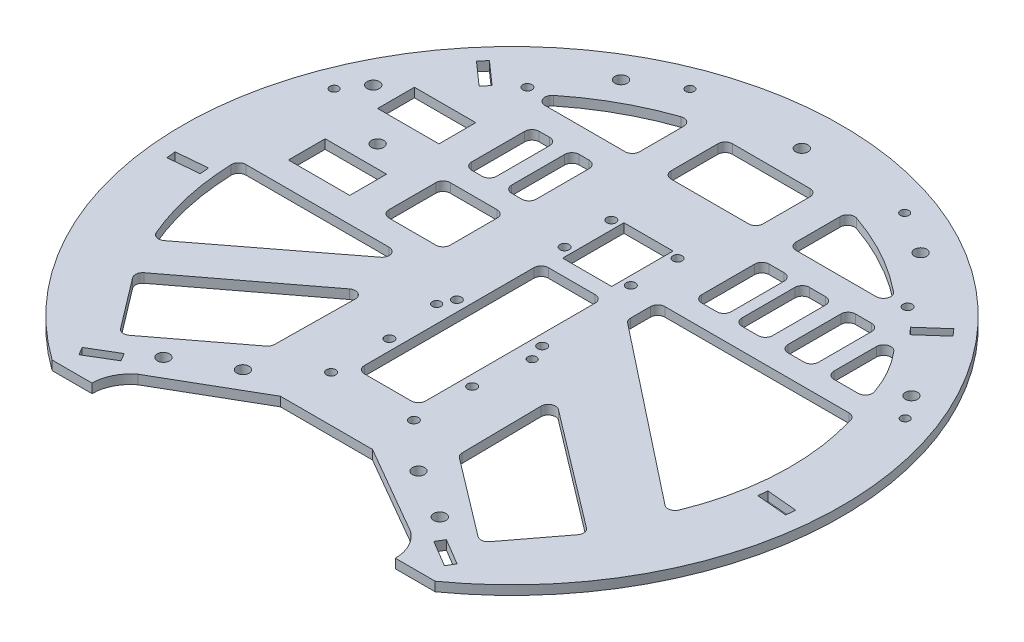
SolidWorks part; units mm, degrees
ref_plane "Front Plane" through (0, 0, 0) normal (0, 0, 1) x (1, 0, 0)
ref_plane "Top Plane" through (0, 0, 0) normal (0, 1, 0) x (1, 0, 0)
ref_plane "Right Plane" through (0, 0, 0) normal (1, 0, 0) x (0, 0, -1)
sketch "Sketch3" plane through (0, 0, 0) normal (0, 1, 0) x (1, 0, 0)
  line L0 (62.45, -87.5) -> (49.45, -87.5)
  line L5 (7.6386, -40.5) -> (-7.6386, -40.5)
  line L6 (-10, -38.1386) -> (-10, 17.1386)
  line L7 (-7.6386, 19.5) -> (7.6386, 19.5)
  line L8 (10, 17.1386) -> (10, -38.1386)
  line L9 (63.1175, 36.8614) -> (63.1175, 54.1386)
  line L10 (0, 107.5) -> (0, -126.7072) construction
  line L13 (-34.0506, -18.9275) -> (-72.1189, -47.8376)
  line L14 (-37.9392, -4.9265) -> (-77.8771, -35.4832)
  line L15 (-39.3741, -0.6896) -> (-86.0847, -0.6896)
  line L16 (-30, 9.8718) -> (-30, 25.149)
  line L17 (-32.3614, 27.5104) -> (-47.6386, 27.5104)
  line L18 (-50, 25.149) -> (-50, 9.8718)
  line L19 (-47.6386, 7.5104) -> (-32.3614, 7.5104)
  line L20 (-60.4278, 7.5104) -> (-60.4278, 19.5104)
  line L21 (-60.4278, 19.5104) -> (-80.4278, 19.5104)
  line L22 (-80.4278, 19.5104) -> (-80.4278, 7.5104)
  line L23 (-80.4278, 7.5104) -> (-60.4278, 7.5104)
  line L28 (-60.4278, 36.6052) -> (-60.4278, 48.6052)
  line L29 (-60.4278, 48.6052) -> (-80.4278, 48.6052)
  line L30 (-30.2612, -20.8387) -> (-30.5985, -46.8494)
  line L31 (-80.4278, 48.6052) -> (-80.4278, 36.6052)
  line L32 (-80.4278, 36.6052) -> (-60.4278, 36.6052)
  line L33 (-41.8825, 36.8614) -> (-41.8825, 54.1386)
  line L34 (-44.2439, 56.5) -> (-47.6386, 56.5)
  line L35 (-50, 54.1386) -> (-50, 36.8614)
  line L36 (-47.6386, 34.5) -> (-44.2439, 34.5)
  line L41 (8, 24.5) -> (-8, 24.5)
  line L43 (-8, 44.5) -> (8, 44.5)
  line L44 (8, 44.5) -> (8, 24.5)
  line L50 (20, 18.6456) -> (20, 25.1386)
  line L51 (22.3614, 27.5) -> (82.3868, 27.5)
  line L52 (78.3282, 34.5) -> (70.479, 34.5)
  line L53 (68.1175, 36.8614) -> (68.1175, 50.6943)
  line L54 (60.7561, 56.5) -> (55.479, 56.5)
  line L55 (53.1175, 54.1386) -> (53.1175, 36.8614)
  line L56 (55.479, 34.5) -> (60.7561, 34.5)
  line L57 (45.7561, 34.5) -> (40.479, 34.5)
  line L58 (38.1175, 36.8614) -> (38.1175, 54.1386)
  line L59 (40.479, 56.5) -> (45.7561, 56.5)
  line L60 (30.2612, -20.8387) -> (30.5985, -46.8494)
  line L68 (-25.5, 67.1081) -> (-25.5, 81.5083)
  line L81 (34.0506, -18.9275) -> (72.1189, -47.8376)
  line L82 (78.4833, -28.5913) -> (20.8997, 16.7909)
  line L83 (-54.0033, 64.7467) -> (-27.8614, 64.7467)
  line L85 (48.1175, 36.8614) -> (48.1175, 54.1386)
  line L86 (25.5, 67.1081) -> (25.5, 81.5083)
  line L87 (54.0033, 64.7467) -> (27.8614, 64.7467)
  line L88 (-15, -60.5) -> (-44.4449, -77.5)
  line L89 (-15, -60.5) -> (15, -60.5)
  line L90 (15, -60.5) -> (44.4449, -77.5)
  line L91 (-49.45, -87.5) -> (-62.45, -87.5)
  line L95 (-31.5315, -48.6993) -> (-56.858, -67.9329)
  line L96 (-72.5713, -51.1463) -> (-60.1667, -67.4805)
  line L97 (31.5315, -48.6993) -> (56.858, -67.9329)
  line L98 (72.5713, -51.1463) -> (60.1667, -67.4805)
  line L104 (-36.9576, 54.1386) -> (-36.9576, 36.8614)
  line L105 (-34.5962, 56.5) -> (-31.3191, 56.5)
  line L106 (-34.5962, 34.5) -> (-31.3191, 34.5)
  line L107 (-28.9576, 54.1386) -> (-28.9576, 36.8614)
  line L112 (34.6175, 54.1386) -> (34.6175, 36.8614)
  line L113 (32.2561, 56.5) -> (27.3488, 56.5)
  line L114 (32.2561, 34.5) -> (27.3488, 34.5)
  line L115 (24.9873, 54.1386) -> (24.9873, 36.8614)
  line L116 (-15, 66.8614) -> (-15, 82.1386)
  line L117 (-12.6386, 64.5) -> (12.6386, 64.5)
  line L118 (-12.6386, 84.5) -> (12.6386, 84.5)
  line L119 (15, 66.8614) -> (15, 82.1386)
  line L120 (-8, 44.5) -> (-8, 24.5)
  arc A5 (-62.45, -87.5) -> (62.45, -87.5) centre (0, 0) cw
  arc A9 (-81.4863, -34.5291) -> (-88.4446, -3.1347) centre (0, 0) cw
  arc A10 (-55.4838, 68.9478) -> (-28.6252, 83.7427) centre (0, 0) cw
  arc A12 (72.2775, 52.2245) -> (80.5643, 37.6206) centre (38.2127, 23.2419) cw
  arc A13 (82.1308, -27.6301) -> (84.6469, 25.8229) centre (8.0792, 2.6412) ccw
  circle A22 centre (-28.6195, -59.1256) radius 2
  circle A25 centre (-45.0553, -68.6148) radius 2
  circle A27 centre (28.6192, -59.1254) radius 2
  circle A31 centre (87.7501, 42.499) radius 2
  circle A34 centre (48.8392, 84.3859) radius 2
  circle A37 centre (-15.5888, -8.9994) radius 1.4
  circle A39 centre (-70.4278, 26.6052) radius 2
  circle A41 centre (-87.7498, 42.4997) radius 2
  circle A45 centre (-48.8392, 84.3859) radius 2
  arc A46 (55.4838, 68.9478) -> (28.6252, 83.7427) centre (0, 0) ccw
  circle A47 centre (45.0549, -68.6146) radius 2
  circle A48 centre (-62, 67) radius 1.5
  circle A50 centre (62, 67) radius 1.5
  circle A51 centre (0, 94.5) radius 2
  arc A55 (-49.45, -87.5) -> (-44.4449, -77.5) centre (-36.9576, -87.5) cw
  arc A56 (49.45, -87.5) -> (44.4449, -77.5) centre (36.9576, -87.5) ccw
  circle A58 centre (15.5885, -8.9999) radius 1.4
  circle A59 centre (13.5, -26.5) radius 1.5
  circle A60 centre (-13.5, -26.5) radius 1.5
  circle A61 centre (-13.5, -4.5) radius 1.5
  circle A62 centre (13.5, -3.6504) radius 1.5
  circle A63 centre (-10.795, 43.18) radius 1.5
  circle A64 centre (10.795, 43.18) radius 1.5
  circle A65 centre (-10.795, 27.94) radius 1.5
  circle A66 centre (10.795, 27.94) radius 1.5
  circle A67 centre (-13.5, -45.5) radius 1.5
  circle A68 centre (13.5, -45.5) radius 1.5
  arc A69 (12.6386, 64.5) -> (15, 66.8614) centre (12.6386, 66.8614) ccw
  arc A70 (12.6386, 84.5) -> (15, 82.1386) centre (12.6386, 82.1386) cw
  arc A71 (-15, 66.8614) -> (-12.6386, 64.5) centre (-12.6386, 66.8614) ccw
  arc A72 (-15, 82.1386) -> (-12.6386, 84.5) centre (-12.6386, 82.1386) cw
  arc A73 (-27.8614, 64.7467) -> (-25.5, 67.1081) centre (-27.8614, 67.1081) ccw
  arc A74 (-55.4838, 68.9478) -> (-54.0033, 64.7467) centre (-54.0033, 67.1081) ccw
  arc A75 (-28.6252, 83.7427) -> (-25.5, 81.5083) centre (-27.8614, 81.5083) cw
  arc A76 (78.3282, 34.5) -> (80.5643, 37.6206) centre (78.3282, 36.8614) ccw
  arc A77 (68.1175, 36.8614) -> (70.479, 34.5) centre (70.479, 36.8614) ccw
  arc A78 (68.1175, 50.6943) -> (72.2775, 52.2245) centre (70.479, 50.6943) cw
  arc A79 (60.7561, 56.5) -> (63.1175, 54.1386) centre (60.7561, 54.1386) cw
  arc A80 (60.7561, 34.5) -> (63.1175, 36.8614) centre (60.7561, 36.8614) ccw
  arc A81 (53.1175, 36.8614) -> (55.479, 34.5) centre (55.479, 36.8614) ccw
  arc A82 (53.1175, 54.1386) -> (55.479, 56.5) centre (55.479, 54.1386) cw
  arc A83 (45.7561, 56.5) -> (48.1175, 54.1386) centre (45.7561, 54.1386) cw
  arc A84 (45.7561, 34.5) -> (48.1175, 36.8614) centre (45.7561, 36.8614) ccw
  arc A85 (38.1175, 36.8614) -> (40.479, 34.5) centre (40.479, 36.8614) ccw
  arc A86 (38.1175, 54.1386) -> (40.479, 56.5) centre (40.479, 54.1386) cw
  arc A87 (32.2561, 34.5) -> (34.6175, 36.8614) centre (32.2561, 36.8614) ccw
  arc A88 (32.2561, 56.5) -> (34.6175, 54.1386) centre (32.2561, 54.1386) cw
  arc A89 (24.9873, 36.8614) -> (27.3488, 34.5) centre (27.3488, 36.8614) ccw
  arc A90 (24.9873, 54.1386) -> (27.3488, 56.5) centre (27.3488, 54.1386) cw
  arc A91 (-32.3614, 27.5104) -> (-30, 25.149) centre (-32.3614, 25.149) cw
  arc A92 (-32.3614, 7.5104) -> (-30, 9.8718) centre (-32.3614, 9.8718) ccw
  arc A93 (-47.6386, 7.5104) -> (-50, 9.8718) centre (-47.6386, 9.8718) cw
  arc A94 (-50, 25.149) -> (-47.6386, 27.5104) centre (-47.6386, 25.149) cw
  arc A95 (-31.3191, 56.5) -> (-28.9576, 54.1386) centre (-31.3191, 54.1386) cw
  arc A96 (-31.3191, 34.5) -> (-28.9576, 36.8614) centre (-31.3191, 36.8614) ccw
  arc A97 (-36.9576, 36.8614) -> (-34.5962, 34.5) centre (-34.5962, 36.8614) ccw
  arc A98 (-36.9576, 54.1386) -> (-34.5962, 56.5) centre (-34.5962, 54.1386) cw
  arc A99 (-44.2439, 56.5) -> (-41.8825, 54.1386) centre (-44.2439, 54.1386) cw
  arc A100 (-44.2439, 34.5) -> (-41.8825, 36.8614) centre (-44.2439, 36.8614) ccw
  arc A101 (-47.6386, 34.5) -> (-50, 36.8614) centre (-47.6386, 36.8614) cw
  arc A102 (-50, 54.1386) -> (-47.6386, 56.5) centre (-47.6386, 54.1386) cw
  arc A103 (54.0033, 64.7467) -> (55.4838, 68.9478) centre (54.0033, 67.1081) ccw
  arc A104 (27.8614, 64.7467) -> (25.5, 67.1081) centre (27.8614, 67.1081) cw
  arc A105 (25.5, 81.5083) -> (28.6252, 83.7427) centre (27.8614, 81.5083) cw
  arc A106 (-39.3741, -0.6896) -> (-37.9392, -4.9265) centre (-39.3741, -3.051) cw
  arc A107 (-77.8771, -35.4832) -> (-81.4863, -34.5291) centre (-79.312, -33.6078) cw
  arc A108 (-88.4446, -3.1347) -> (-86.0847, -0.6896) centre (-86.0847, -3.051) cw
  arc A109 (-72.5713, -51.1463) -> (-72.1189, -47.8376) centre (-70.6907, -49.7182) cw
  arc A110 (-60.1667, -67.4805) -> (-56.858, -67.9329) centre (-58.2862, -66.0523) ccw
  arc A111 (-31.5315, -48.6993) -> (-30.5985, -46.8494) centre (-32.9597, -46.8188) ccw
  arc A112 (-34.0506, -18.9275) -> (-30.2612, -20.8387) centre (-32.6224, -20.8081) cw
  arc A113 (-10, 17.1386) -> (-7.6386, 19.5) centre (-7.6386, 17.1386) cw
  arc A114 (7.6386, 19.5) -> (10, 17.1386) centre (7.6386, 17.1386) cw
  arc A115 (10, -38.1386) -> (7.6386, -40.5) centre (7.6386, -38.1386) cw
  arc A116 (-10, -38.1386) -> (-7.6386, -40.5) centre (-7.6386, -38.1386) ccw
  arc A117 (72.1189, -47.8376) -> (72.5713, -51.1463) centre (70.6907, -49.7182) cw
  arc A118 (56.858, -67.9329) -> (60.1667, -67.4805) centre (58.2862, -66.0523) ccw
  arc A119 (30.5985, -46.8494) -> (31.5315, -48.6993) centre (32.9597, -46.8188) ccw
  arc A120 (30.2612, -20.8387) -> (34.0506, -18.9275) centre (32.6224, -20.8081) cw
  arc A121 (78.4833, -28.5913) -> (82.1308, -27.6301) centre (79.945, -26.7366) ccw
  arc A122 (84.6469, 25.8229) -> (82.3868, 27.5) centre (82.3868, 25.1386) ccw
  arc A123 (20, 18.6456) -> (20.8997, 16.7909) centre (22.3614, 18.6456) ccw
  arc A124 (20, 25.1386) -> (22.3614, 27.5) centre (22.3614, 25.1386) cw
  point P45 (0, -60.5)
  point P48 (0, 64.6145)
  point P49 (0, 84.5)
  point P51 (0, 84.7467)
  point P62 (0, 107.5)
  point P90 (0, 24.5)
  point P91 (0, 44.5)
  point P93 (15, 64.5)
  point P97 (15, 84.5)
  point P104 (-25.5, 64.7467)
  point P109 (-60.3334, 64.7467)
  point P113 (-25.5, 84.7467)
  point P150 (38.1175, 34.5)
  point P155 (34.6175, 34.5)
  point P172 (-28.9576, 56.5)
  point P179 (-36.9576, 56.5)
  point P190 (60.3334, 64.7467)
  point P193 (25.5, 64.7467)
  point P196 (25.5, 84.7467)
  point P202 (-80.2546, -37.3023)
  point P209 (-73.9995, -49.2657)
  point P212 (-58.7386, -69.3611)
  point P215 (-30.6134, -48.0021)
  point P218 (-30.1985, -16.0021)
  point P233 (73.9995, -49.2657)
  point P238 (58.7386, -69.3611)
  point P243 (30.6134, -48.0021)
  point P246 (30.1985, -16.0021)
  point P249 (80.8953, -30.4921)
  point P256 (20, 17.5)
  point P263 (20, 27.5)
  dimension "D8" = 3
  dimension "D9" = 91.2853
  dimension "D10" = 30
  dimension "D11" = 27
  dimension "D12" = 150
  dimension "D13" = 34
  dimension "D14" = 13
  dimension "D15" = 155
  dimension "D16" = 8
  dimension "D17" = 8
  dimension "D18" = 13.5
  dimension "D19" = 34
  dimension "D20" = 8
  dimension "D21" = 8
  dimension "D22" = 20
  dimension "D6" = 3
  dimension "D7" = 62
  dimension "D23" = 3
  dimension "D24" = 3
  dimension "D27" = 8
  dimension "D33" = 107.5
  dimension "D40" = 19
  dimension "D28" = 23
  dimension "D42" = 13.5
  dimension "D43" = 22
  dimension "D44" = 13.5
  dimension "D45" = 3
  dimension "D46" = 3
  dimension "D47" = 3
  dimension "D48" = 3
  dimension "D49" = 15.24
  dimension "D50" = 10.795
  dimension "D51" = 10.795
  dimension "D52" = 22.8496
  dimension "D55" = 3
  dimension "D54" = 27
  dimension "D56" = 3
  dimension "D57" = 13.5
  dimension "D58" = 13.5
  dimension "D59" = 15
  dimension "D60" = 15
  dimension "D63" = 2.3614
  dimension "D64" = 2.3614
  dimension "D65" = 2.3614
  dimension "D67" = 8.44
  dimension "D3" = 10
  dimension "D4" = 55
  dimension "D5" = 3.5
  dimension "D25" = 32
  dimension "D26" = 8
  dimension "D29" = 20
  dimension "D30" = 25.5
  dimension "D31" = 150
  dimension "D32" = 20
  dimension "D34" = 20
  dimension "D35" = 20
  dimension "D36" = 13.5
  dimension "D37" = 13.5
  dimension "D38" = 8.2
  dimension "D39" = 8.2
  dimension "D41" = 98.9
  dimension "D53" = 20
  dimension "D61" = 20
  dimension "D62" = 12
  dimension "D66" = 5
extrude "Tapa" add sketch "Sketch3" along normal blind 3
sketch "Sketch4" plane through (0, 3, 0) normal (0, 1, 0) x (1, 0, 0)
  line L0 (0, 0) -> (0, -88.7396) construction
  circle A1 centre (-93.1034, 35.1) radius 1.4
  circle A5 centre (35, 93.0342) radius 1.4
  circle A7 centre (58, -78.9937) radius 1.4
  circle A8 centre (0, 0) radius 107.5
  arc A9 (62.45, -87.5) -> (-62.45, -87.5) centre (0, 0) ccw construction
  circle A10 centre (-35, 93.0342) radius 1.4
  circle A11 centre (93.1034, 35.1) radius 1.4
  circle A13 centre (-58, -78.9937) radius 1.4
  dimension "D2" = 2.8
  dimension "D4" = 99.4
  dimension "D6" = 99.5
  dimension "D7" = 2.8
  dimension "D10" = 98
  dimension "D12" = 58
  dimension "D13" = 2.8
  dimension "D5" = 35
  dimension "D11" = 35.1
extrude "Holes de soportes" cut sketch "Sketch4" against normal blind 30
sketch "Sketch6" plane through (0, 3, 0) normal (0, 1, 0) x (1, 0, 0)
  line L0 (0, 138.3374) -> (0, -97.2111) construction
  line L1 (90.9, -10.7432) -> (91.1724, -7.7556)
  line L2 (101.1724, -8.6674) -> (91.1724, -7.7556)
  line L3 (100.9, -11.655) -> (90.9, -10.7432)
  line L4 (100.9, -11.655) -> (101.1724, -8.6674)
  line L5 (70.2156, 59.4796) -> (68.2269, 61.7257)
  line L6 (75.7142, 68.3546) -> (68.2269, 61.7257)
  line L7 (77.7028, 66.1084) -> (70.2156, 59.4796)
  line L8 (77.7028, 66.1084) -> (75.7142, 68.3546)
  line L9 (-100.9, -11.655) -> (-101.1724, -8.6674)
  line L10 (-100.9, -11.655) -> (-90.9, -10.7432)
  line L11 (-101.1724, -8.6674) -> (-91.1724, -7.7556)
  line L12 (-90.9, -10.7432) -> (-91.1724, -7.7556)
  line L13 (-77.7028, 66.1084) -> (-75.7142, 68.3546)
  line L14 (-75.7142, 68.3546) -> (-68.2269, 61.7257)
  line L15 (-77.7028, 66.1084) -> (-70.2156, 59.4796)
  line L16 (-70.2156, 59.4796) -> (-68.2269, 61.7257)
  line L17 (-61.1276, -79.0484) -> (-52.5405, -73.9239)
  line L18 (-52.5405, -73.9239) -> (-51.0031, -76.5)
  line L19 (-51.0031, -76.5) -> (-59.5902, -81.6246)
  line L20 (-59.5902, -81.6246) -> (-61.1276, -79.0484)
  line L21 (-62.45, -87.5) -> (-49.45, -87.5) construction
  line L22 (59.5902, -81.6246) -> (61.1276, -79.0484)
  line L23 (51.0031, -76.5) -> (59.5902, -81.6246)
  line L24 (52.5405, -73.9239) -> (51.0031, -76.5)
  line L25 (61.1276, -79.0484) -> (52.5405, -73.9239)
  circle A0 centre (0, 0) radius 107.5
  arc A1 (62.45, -87.5) -> (-62.45, -87.5) centre (0, 0) ccw construction
  dimension "D1" = 92
  dimension "D2" = 91.5
  dimension "D3" = 3
  dimension "D4" = 3
  dimension "D5" = 10
  dimension "D6" = 10
  dimension "D7" = 3
  dimension "D8" = 10
  dimension "D9" = 10
  dimension "D10" = 3
  dimension "D11" = 77.7028
  dimension "D12" = 75.7142
  dimension "D13" = 68.2269
  dimension "D14" = 3
  dimension "D15" = 91.1724
  dimension "D16" = 100.9
  dimension "D17" = 101.1724
  dimension "D18" = 3
  dimension "D19" = 10
  dimension "D20" = 3
  dimension "D21" = 93
  dimension "D22" = 11
extrude "Cut-Extrude1" cut sketch "Sketch6" against normal blind 10 contours L20 L19 L18 L17 | L22 L25 L24 L23 | L2 L1 L3 L4 | L9 L11 L12 L10 | L13 L14 L16 L15 | L5 L6 L8 L7
equation "\"10.2t\"=10.19"
